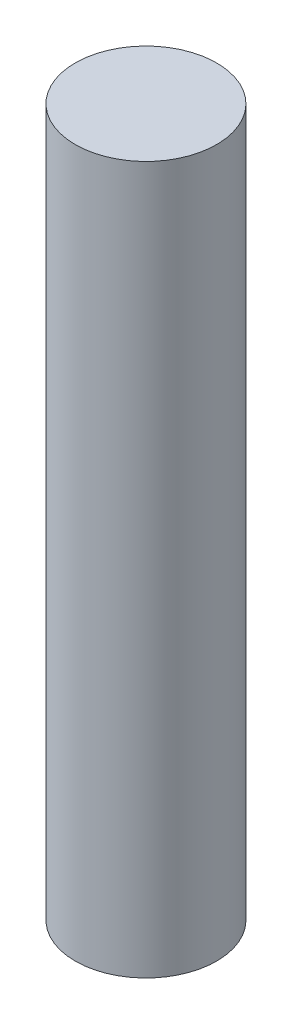
SolidWorks part; units mm, degrees
material "AISI 1020"
ref_plane "Front Plane" through (0, 0, 0) normal (0, 0, 1) x (1, 0, 0)
ref_plane "Top Plane" through (0, 0, 0) normal (0, 1, 0) x (1, 0, 0)
ref_plane "Right Plane" through (0, 0, 0) normal (1, 0, 0) x (0, 0, -1)
sketch "Sketch1" plane through (0, 0, 0) normal (0, 1, 0) x (1, 0, 0)
  line L0 (0, 0) -> (0, -29.6379) construction
  circle A0 centre (0, -10.5) radius 1.5
  dimension "D1" = 10.5
  dimension "D2" = 3
extrude "Boss-Extrude1" add sketch "Sketch1" along normal mid plane 15
